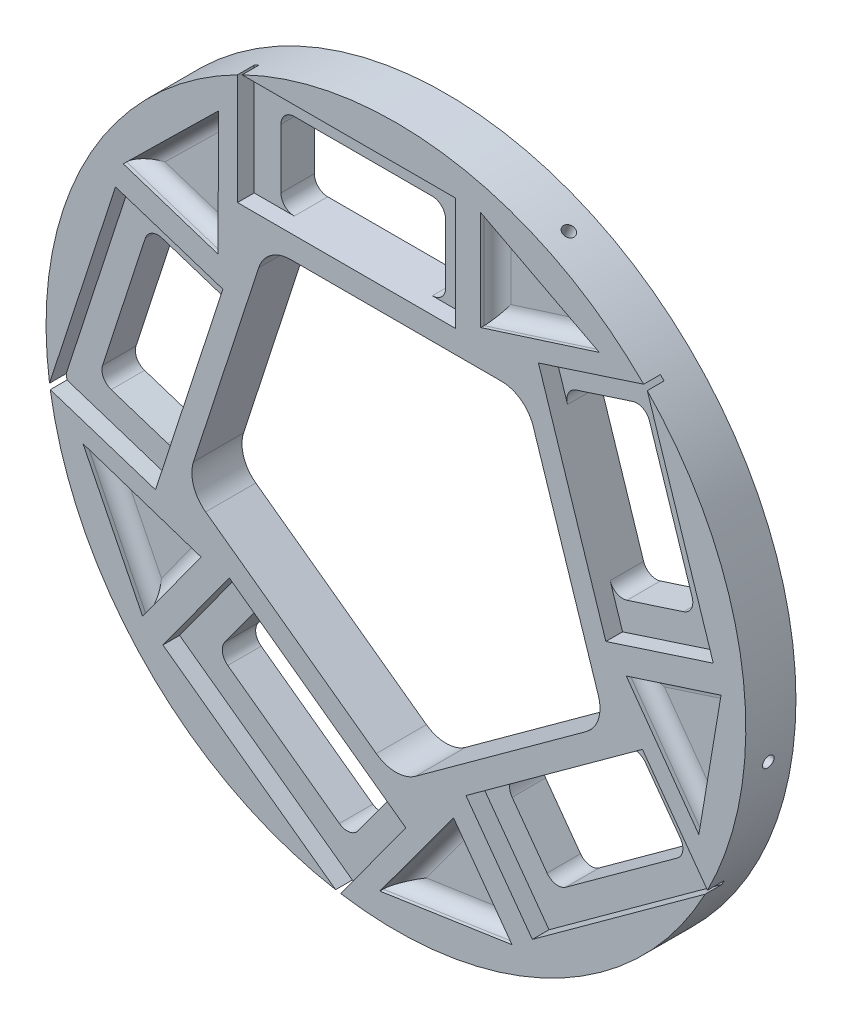
SolidWorks part; units mm, degrees
material "ABS PC"
ref_plane "Front Plane" through (0, 0, 0) normal (0, 0, 1) x (1, 0, 0)
ref_plane "Top Plane" through (0, 0, 0) normal (0, 1, 0) x (1, 0, 0)
ref_plane "Right Plane" through (0, 0, 0) normal (1, 0, 0) x (0, 0, -1)
sketch "Sketch1" plane through (0, 0, 0) normal (0, 0, 1) x (1, 0, 0)
  circle A0 centre (0, 0) radius 66.4845
  dimension "D1" = 132.969
extrude "Boss-Extrude1" add sketch "Sketch1" along normal blind 9.525
sketch "Sketch2" plane through (0, 0, 9.525) normal (0, 0, 1) x (1, 0, 0)
  line L1 (24.6533, 33.9323) -> (-24.6533, 33.9323)
  line L2 (-24.6533, 33.9323) -> (-39.8898, -12.961)
  line L3 (-39.8898, -12.961) -> (0, -41.9426)
  line L4 (0, -41.9426) -> (39.8898, -12.961)
  line L5 (39.8898, -12.961) -> (24.6533, 33.9323)
  circle A0 centre (0, 0) radius 33.9323 construction
  dimension "D1" = 33.9323
extrude "Cut-Extrude1" cut sketch "Sketch2" against normal through all
fillet "Fillet1" radius 6.35 5 edges at (-39.8898, -12.961, 4.7625) (0, -41.9426, 4.7625) (39.8898, -12.961, 4.7625) (24.6533, 33.9323, 4.7625) (-24.6533, 33.9323, 4.7625)
sketch "Sketch3" plane through (0, 0, 9.525) normal (0, 0, 1) x (1, 0, 0)
  line L0 (16.1109, 40.7937) -> (16.1109, 59.7167)
  line L1 (11.3484, 38.2537) -> (-30.1056, 38.2537)
  line L2 (11.3484, 38.2537) -> (11.3484, 59.7167)
  line L3 (11.3484, 59.7167) -> (-30.1056, 59.7167)
  line L4 (-30.1056, 38.2537) -> (-30.1056, 59.7167)
  line L5 (16.1109, 59.7167) -> (38.6331, 47.9732)
  line L6 (38.6331, 47.9732) -> (16.1109, 40.7937)
  dimension "D1" = 41.454
  dimension "D2" = 21.463
  dimension "D3" = 59.7167
  dimension "D4" = 30.1056
  dimension "D5" = 4.7625
  dimension "D6" = 2.54
  dimension "D7" = 25.4
  dimension "D8" = 61.595
extrude "Cut-Extrude5" cut sketch "Sketch3" against normal offset from surface (3.175 mm away) 6.35 up to face at (0, 0, 0)
sketch "Sketch4" plane through (0, 0, 6.35) normal (0, 0, 1) x (1, 0, 0)
  line L0 (11.3484, 38.2537) -> (-30.1056, 38.2537) construction
  line L1 (11.3484, 59.7167) -> (-29.2251, 59.7167) construction
  line L2 (-30.1056, 59.2777) -> (-30.1056, 38.2537) construction
  line L3 (-25.0256, 38.2537) -> (6.2684, 38.2537)
  line L4 (-25.0256, 38.2537) -> (-25.0256, 54.6367)
  line L5 (-25.0256, 54.6367) -> (6.2684, 54.6367)
  line L6 (6.2684, 38.2537) -> (6.2684, 54.6367)
  line L7 (-25.0256, 38.2537) -> (-30.1056, 38.2537) construction
  line L8 (6.2684, 38.2537) -> (11.3484, 38.2537) construction
  line L9 (-29.2251, 59.7167) -> (11.3484, 59.7167) construction
  line L10 (11.3484, 59.7167) -> (11.3484, 38.2537) construction
  circle A0 centre (-19.9456, 49.1249) radius 3.9688 construction
  dimension "D3" = 7.9375
  dimension "D1" = 10.5918
  dimension "D2" = 10.16
  dimension "D4" = 5.08
  dimension "D5" = 5.08
extrude "Cut-Extrude6" cut sketch "Sketch4" against normal through all
fillet "Fillet2" radius 2.54 7 edges at (-25.0256, 38.2537, 3.175) (6.2684, 38.2537, 3.175) (6.2684, 54.6367, 3.175) (-25.0256, 54.6367, 3.175) (16.1109, 50.2552, 6.35) (27.372, 53.8449, 6.35) (27.372, 44.3834, 6.35)
sketch "Sketch5" plane through (0, 0, 9.525) normal (0, 0, 1) x (1, 0, 0)
  line L0 (0, 0) -> (0, 33.9323) construction
  line L1 (20.0397, 33.9323) -> (-20.0397, 33.9323) construction
  line L2 (0, 33.9323) -> (0, 66.4845) construction
  line L3 (0, 0) -> (28.0976, 60.2554) construction
  arc A0 (-30.1056, 59.2777) -> (-29.2251, 59.7167) centre (0, 0) ccw construction
  dimension "D1" = 25
ref_plane "Plane3" through (28.0976, 60.2554, 9.525) normal (0.4226, 0.9063, 0) x (0, 0, 1)
sketch "Sketch6" plane through (28.0976, 60.2554, 9.525) normal (0.4226, 0.9063, 0) x (0, 0, 1)
  line L0 (0, 0) -> (-4.7625, 0) construction
  line L1 (-4.7625, 0) -> (-9.525, 0) construction
  dimension "D1" = 4.7625
hole_wizard "#44 (0.086) Diameter Hole1" positions "Sketch8" profile "Sketch7" hole size "#44" standard "ANSI Inch"
sketch "Sketch8" plane through (28.0976, 60.2554, 9.525) normal (0.4226, 0.9063, 0) x (0, 0, 1)
  point P0 (-4.7625, 0)
sketch "Sketch7" plane through (28.0976, 60.2554, 4.7625) normal (0, 0, 1) x (-0.9063, 0.4226, 0)
  line L0 (0, 0) -> (0, 14.6263)
  line L1 (0, 14.6263) -> (1.0922, 13.97)
  line L2 (1.0922, 13.97) -> (1.0922, 0)
  line L5 (1.0922, 0) -> (0, 0)
  line L10 (0, 14.6263) -> (-1.0922, 13.97) construction
  line L11 (0, -6.35) -> (0, 107.95) construction
  dimension "Hole Dia." = 2.1844
  dimension "Hole Depth" = 13.97
  dimension "Drill Angle" = 118
pattern_circular "CirPattern1" count 5 over 360 about axis through (0, 0, 0) along (0, 0, 1) of "Cut-Extrude5", "Cut-Extrude6", "#44 (0.086) Diameter Hole1", "Fillet2"
